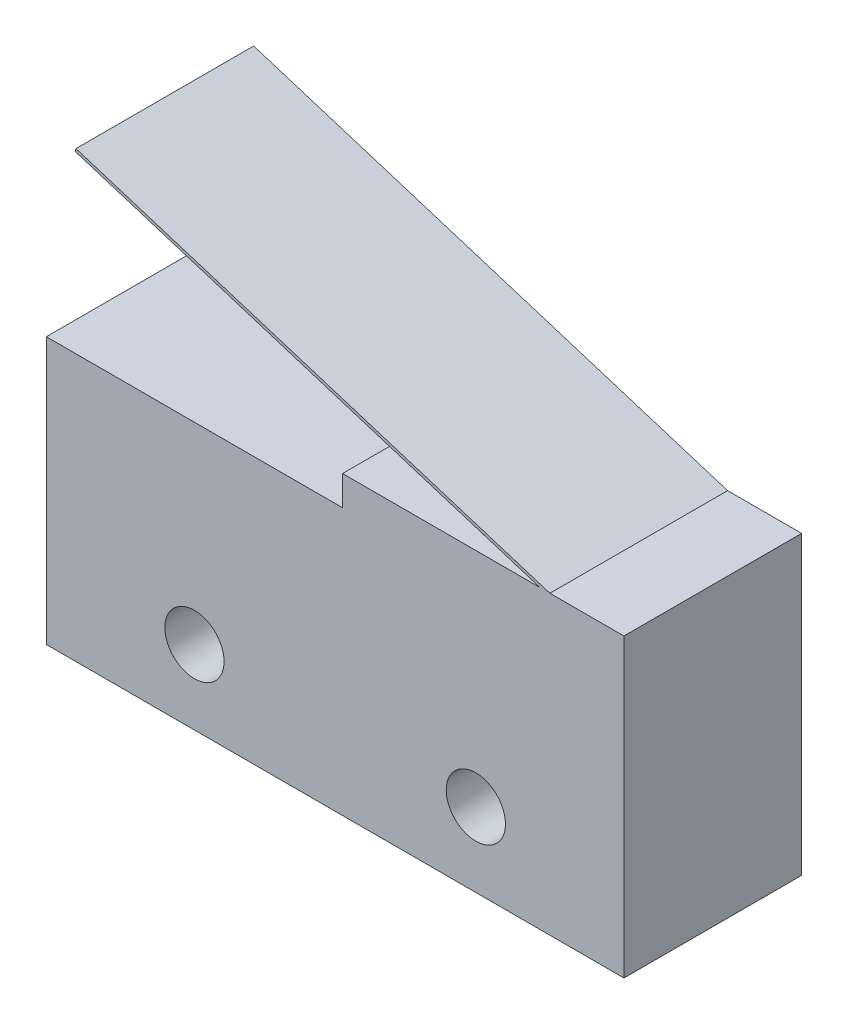
SolidWorks part; units mm, degrees
ref_plane "Front Plane" through (0, 0, 0) normal (0, 0, 1) x (1, 0, 0)
ref_plane "Top Plane" through (0, 0, 0) normal (0, 1, 0) x (1, 0, 0)
ref_plane "Right Plane" through (0, 0, 0) normal (1, 0, 0) x (0, 0, -1)
sketch "Sketch1" plane through (0, 0, 0) normal (0, 0, 1) x (1, 0, 0)
  line L0 (-9.75, 4) -> (0.25, 4)
  line L1 (-9.75, -5) -> (9.75, -5)
  line L2 (-9.75, -5) -> (-9.75, 4)
  line L3 (0.25, 5) -> (9.75, 5)
  line L4 (9.75, -5) -> (9.75, 5)
  line L5 (0, 5) -> (0, -5) construction
  line L6 (-9.75, 0) -> (9.75, 0) construction
  line L7 (0.25, 4) -> (0.25, 5)
  line L8 (-9.75, 4) -> (-9.75, 5) construction
  line L9 (-9.75, 5) -> (0, 5) construction
  line L10 (0, 5) -> (0.25, 5) construction
  circle A0 centre (-4.75, -2.5) radius 1
  circle A1 centre (4.75, -2.5) radius 1
  point P0 (0, 0)
  point P6 (0, 0)
  dimension "D5" = 2
  dimension "D1" = 10
  dimension "D2" = 19.5
  dimension "D3" = 5
  dimension "D4" = 2.5
  dimension "D6" = 1
  dimension "D7" = 10
extrude "Boss-Extrude1" add sketch "Sketch1" along normal blind 6
sketch "Sketch2" plane through (0, 0, 0) normal (0, 0, -1) x (-1, 0, 0)
  line L0 (-7.25, 5) -> (8.75, 10)
  line L1 (-9.75, 5) -> (-0.25, 5) construction
  line L2 (8.75, 10) -> (8.7798, 9.9046)
  line L3 (8.7798, 9.9046) -> (-6.9147, 5)
  line L4 (-6.9147, 5) -> (-7.25, 5)
  line L5 (9.75, 4) -> (9.75, -5) construction
  dimension "D1" = 2.5
  dimension "D2" = 1
  dimension "D3" = 0.1
  dimension "D4" = 5
extrude "Boss-Extrude2" add sketch "Sketch2" against normal blind 6
